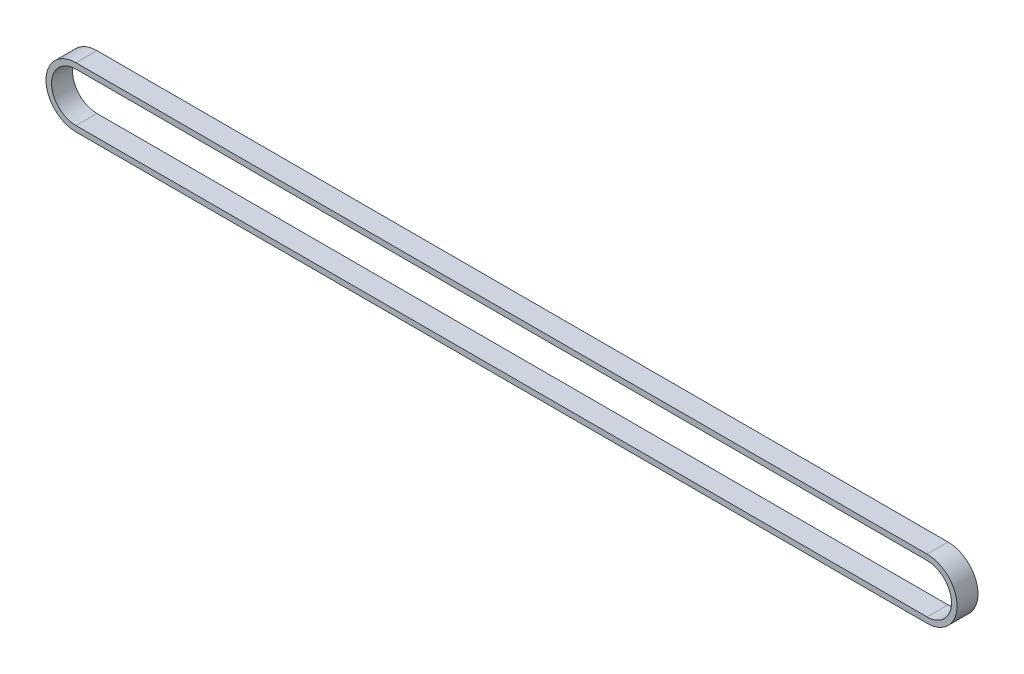
SolidWorks part; units mm, degrees
ref_plane "前视基准面" through (0, 0, 0) normal (0, 0, 1) x (1, 0, 0)
ref_plane "上视基准面" through (0, 0, 0) normal (0, 1, 0) x (1, 0, 0)
ref_plane "右视基准面" through (0, 0, 0) normal (1, 0, 0) x (0, 0, -1)
other "Configuration Table"
sketch "草图1" plane through (0, 0, 0) normal (0, 0, 1) x (1, 0, 0)
  line L0 (0, 0) -> (610, 0) construction
  line L1 (0, 21.5) -> (610, 21.5)
  line L2 (0, -21.5) -> (610, -21.5)
  line L3 (0, 0) -> (610, 0) construction
  line L4 (0, 17.5) -> (610, 17.5)
  line L5 (0, -17.5) -> (610, -17.5)
  arc A0 (0, 21.5) -> (0, -21.5) centre (0, 0) ccw
  arc A1 (610, -21.5) -> (610, 21.5) centre (610, 0) ccw
  arc A2 (0, 17.5) -> (0, -17.5) centre (0, 0) ccw
  arc A3 (610, -17.5) -> (610, 17.5) centre (610, 0) ccw
  point P3 (305, 0)
  point P8 (305, 0)
  dimension "D1" = 610
  dimension "D2" = 35
  dimension "D3" = 4
extrude "凸台-拉伸1" add sketch "草图1" along normal blind 15
